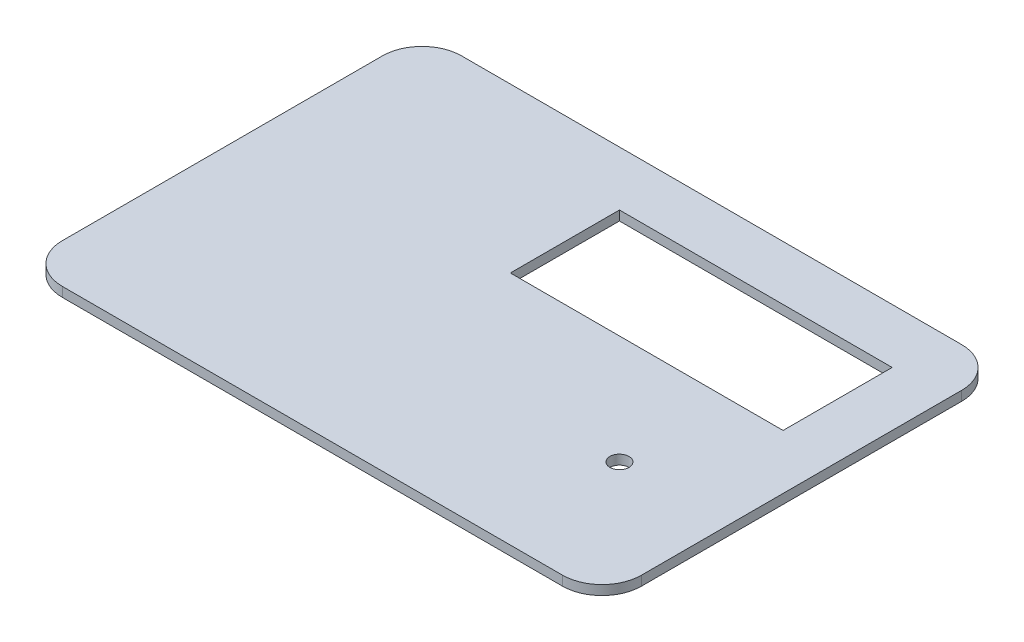
SolidWorks part; units mm, degrees
ref_plane "Front Plane" through (0, 0, 0) normal (0, 0, 1) x (1, 0, 0)
ref_plane "Top Plane" through (0, 0, 0) normal (0, 1, 0) x (1, 0, 0)
ref_plane "Right Plane" through (0, 0, 0) normal (1, 0, 0) x (0, 0, -1)
sketch "Sketch1" plane through (0, 0, 0) normal (0, 1, 0) x (1, 0, 0)
  line L0 (0, -73.2) -> (0, 73.2) construction
  line L1 (-91.7, 73.2) -> (91.7, 73.2)
  line L2 (-106.2, 58.7) -> (-106.2, -58.7)
  line L3 (-91.7, -73.2) -> (91.7, -73.2)
  line L4 (106.2, 58.7) -> (106.2, -58.7)
  line L5 (-106.2, 73.2) -> (106.2, -73.2) construction
  line L6 (-106.2, -73.2) -> (106.2, 73.2) construction
  arc A0 (91.7, -73.2) -> (106.2, -58.7) centre (91.7, -58.7) ccw
  arc A1 (106.2, 58.7) -> (91.7, 73.2) centre (91.7, 58.7) ccw
  arc A2 (-106.2, 58.7) -> (-91.7, 73.2) centre (-91.7, 58.7) cw
  arc A3 (-106.2, -58.7) -> (-91.7, -73.2) centre (-91.7, -58.7) ccw
  point P0 (0, 0)
  dimension "D3" = 14.5
  dimension "D1" = 146.4
  dimension "D2" = 106.2
extrude "Boss-Extrude1" add sketch "Sketch1" along normal blind 3.5
sketch "Sketch2" plane through (0, 3.5, 0) normal (0, 1, 0) x (1, 0, 0)
  line L0 (106.2, -58.7) -> (106.2, 58.7) construction
  line L1 (-13.8, 53.2) -> (86.2, 53.2)
  line L2 (-13.8, 53.2) -> (-13.8, 13.2)
  line L3 (-13.8, 13.2) -> (86.2, 13.2)
  line L4 (86.2, 53.2) -> (86.2, 13.2)
  line L5 (91.7, 73.2) -> (-91.7, 73.2) construction
  circle A0 centre (66.2, -26.8) radius 3.5
  point P6 (17.8414, -18.5938)
  point P7 (0, 0)
  point P13 (-93.7211, -1.3972)
  dimension "D3" = 7
  dimension "D1" = 40
  dimension "D2" = 100
  dimension "D4" = 20
  dimension "D5" = 40
  dimension "D6" = 20
  dimension "D7" = 20
extrude "Cut-Extrude1" cut sketch "Sketch2" against normal blind 3.5
